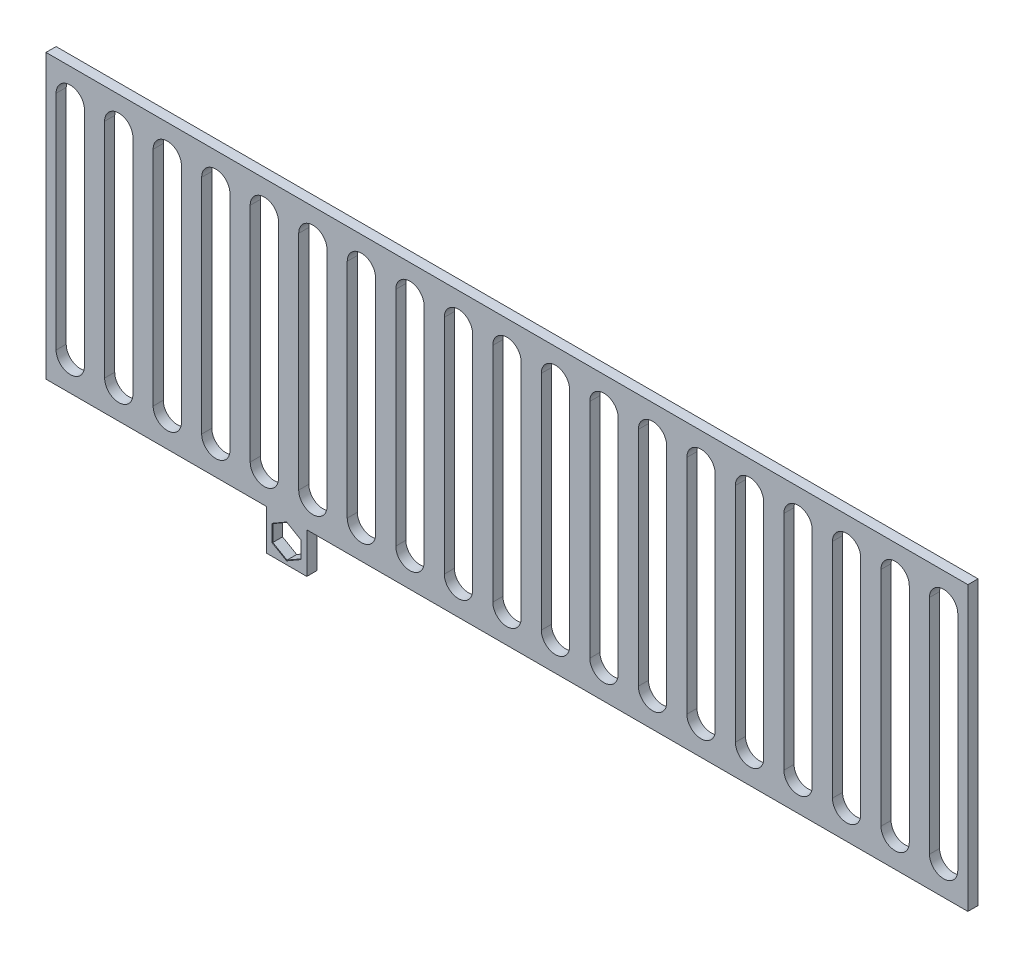
SolidWorks part; units mm, degrees
ref_plane "Plan de face" through (0, 0, 0) normal (0, 0, 1) x (1, 0, 0)
ref_plane "Plan de dessus" through (0, 0, 0) normal (0, 1, 0) x (1, 0, 0)
ref_plane "Plan de droite" through (0, 0, 0) normal (1, 0, 0) x (0, 0, -1)
sketch "Esquisse1" plane through (0, 0, 0) normal (0, 0, 1) x (1, 0, 0)
  line L0 (-108, -27.5) -> (-108, 27.5) construction
  line L1 (-114, 35) -> (114, 35)
  line L2 (-114, 35) -> (-114, -35)
  line L3 (-114, -35) -> (-59.5, -35)
  line L4 (114, 35) -> (114, -35)
  line L5 (-114, 35) -> (114, -35) construction
  line L6 (-114, -35) -> (114, 35) construction
  line L7 (-111.5, -27.5) -> (-111.5, 27.5)
  line L8 (-104.5, -27.5) -> (-104.5, 27.5)
  line L9 (-92.5, -27.5) -> (-92.5, 27.5)
  line L10 (-99.5, -27.5) -> (-99.5, 27.5)
  line L11 (-96, -27.5) -> (-96, 27.5) construction
  line L12 (-80.5, -27.5) -> (-80.5, 27.5)
  line L13 (-87.5, -27.5) -> (-87.5, 27.5)
  line L14 (-84, -27.5) -> (-84, 27.5) construction
  line L15 (-68.5, -27.5) -> (-68.5, 27.5)
  line L16 (-75.5, -27.5) -> (-75.5, 27.5)
  line L17 (-72, -27.5) -> (-72, 27.5) construction
  line L18 (-56.5, -27.5) -> (-56.5, 27.5)
  line L19 (-63.5, -27.5) -> (-63.5, 27.5)
  line L20 (-60, -27.5) -> (-60, 27.5) construction
  line L21 (-44.5, -27.5) -> (-44.5, 27.5)
  line L22 (-51.5, -27.5) -> (-51.5, 27.5)
  line L23 (-48, -27.5) -> (-48, 27.5) construction
  line L24 (-32.5, -27.5) -> (-32.5, 27.5)
  line L25 (-39.5, -27.5) -> (-39.5, 27.5)
  line L26 (-36, -27.5) -> (-36, 27.5) construction
  line L27 (-20.5, -27.5) -> (-20.5, 27.5)
  line L28 (-27.5, -27.5) -> (-27.5, 27.5)
  line L29 (-24, -27.5) -> (-24, 27.5) construction
  line L30 (-8.5, -27.5) -> (-8.5, 27.5)
  line L31 (-15.5, -27.5) -> (-15.5, 27.5)
  line L32 (-12, -27.5) -> (-12, 27.5) construction
  line L33 (3.5, -27.5) -> (3.5, 27.5)
  line L34 (-3.5, -27.5) -> (-3.5, 27.5)
  line L35 (0, -27.5) -> (0, 27.5) construction
  line L36 (15.5, -27.5) -> (15.5, 27.5)
  line L37 (8.5, -27.5) -> (8.5, 27.5)
  line L38 (12, -27.5) -> (12, 27.5) construction
  line L39 (27.5, -27.5) -> (27.5, 27.5)
  line L40 (20.5, -27.5) -> (20.5, 27.5)
  line L41 (24, -27.5) -> (24, 27.5) construction
  line L42 (39.5, -27.5) -> (39.5, 27.5)
  line L43 (32.5, -27.5) -> (32.5, 27.5)
  line L44 (36, -27.5) -> (36, 27.5) construction
  line L45 (51.5, -27.5) -> (51.5, 27.5)
  line L46 (44.5, -27.5) -> (44.5, 27.5)
  line L47 (48, -27.5) -> (48, 27.5) construction
  line L48 (63.5, -27.5) -> (63.5, 27.5)
  line L49 (56.5, -27.5) -> (56.5, 27.5)
  line L50 (60, -27.5) -> (60, 27.5) construction
  line L51 (75.5, -27.5) -> (75.5, 27.5)
  line L52 (68.5, -27.5) -> (68.5, 27.5)
  line L53 (72, -27.5) -> (72, 27.5) construction
  line L54 (87.5, -27.5) -> (87.5, 27.5)
  line L55 (80.5, -27.5) -> (80.5, 27.5)
  line L56 (84, -27.5) -> (84, 27.5) construction
  line L57 (99.5, -27.5) -> (99.5, 27.5)
  line L58 (92.5, -27.5) -> (92.5, 27.5)
  line L59 (96, -27.5) -> (96, 27.5) construction
  line L60 (111.5, -27.5) -> (111.5, 27.5)
  line L61 (104.5, -27.5) -> (104.5, 27.5)
  line L62 (108, -27.5) -> (108, 27.5) construction
  line L69 (-49.5, -35) -> (114, -35)
  line L70 (-59.5, -45) -> (-49.5, -45)
  line L71 (-59.5, -45) -> (-59.5, -35)
  line L73 (-49.5, -45) -> (-49.5, -35)
  line L74 (-59.5, -45) -> (-49.5, -35) construction
  line L75 (-59.5, -35) -> (-49.5, -45) construction
  line L76 (-51, -42.0207) -> (-51, -37.9793)
  line L77 (-51, -37.9793) -> (-54.5, -35.9585)
  line L78 (-54.5, -35.9585) -> (-58, -37.9793)
  line L79 (-58, -37.9793) -> (-58, -42.0207)
  line L80 (-58, -42.0207) -> (-54.5, -44.0415)
  line L81 (-54.5, -44.0415) -> (-51, -42.0207)
  line L82 (123.5, -27.5) -> (123.5, 27.5) [skipped]
  line L83 (128.5, -27.5) -> (128.5, 27.5) [skipped]
  line L84 (135.5, -27.5) -> (135.5, 27.5) [skipped]
  line L85 (116.5, -27.5) -> (116.5, 27.5) [skipped]
  arc A0 (-111.5, -27.5) -> (-104.5, -27.5) centre (-108, -27.5) ccw
  arc A1 (-104.5, 27.5) -> (-111.5, 27.5) centre (-108, 27.5) ccw
  arc A2 (-99.5, -27.5) -> (-92.5, -27.5) centre (-96, -27.5) ccw
  arc A3 (-92.5, 27.5) -> (-99.5, 27.5) centre (-96, 27.5) ccw
  arc A4 (-87.5, -27.5) -> (-80.5, -27.5) centre (-84, -27.5) ccw
  arc A5 (-80.5, 27.5) -> (-87.5, 27.5) centre (-84, 27.5) ccw
  arc A6 (-75.5, -27.5) -> (-68.5, -27.5) centre (-72, -27.5) ccw
  arc A7 (-68.5, 27.5) -> (-75.5, 27.5) centre (-72, 27.5) ccw
  arc A8 (-63.5, -27.5) -> (-56.5, -27.5) centre (-60, -27.5) ccw
  arc A9 (-56.5, 27.5) -> (-63.5, 27.5) centre (-60, 27.5) ccw
  arc A10 (-51.5, -27.5) -> (-44.5, -27.5) centre (-48, -27.5) ccw
  arc A11 (-44.5, 27.5) -> (-51.5, 27.5) centre (-48, 27.5) ccw
  arc A12 (-39.5, -27.5) -> (-32.5, -27.5) centre (-36, -27.5) ccw
  arc A13 (-32.5, 27.5) -> (-39.5, 27.5) centre (-36, 27.5) ccw
  arc A14 (-27.5, -27.5) -> (-20.5, -27.5) centre (-24, -27.5) ccw
  arc A15 (-20.5, 27.5) -> (-27.5, 27.5) centre (-24, 27.5) ccw
  arc A16 (-15.5, -27.5) -> (-8.5, -27.5) centre (-12, -27.5) ccw
  arc A17 (-8.5, 27.5) -> (-15.5, 27.5) centre (-12, 27.5) ccw
  arc A18 (-3.5, -27.5) -> (3.5, -27.5) centre (0, -27.5) ccw
  arc A19 (3.5, 27.5) -> (-3.5, 27.5) centre (0, 27.5) ccw
  arc A20 (8.5, -27.5) -> (15.5, -27.5) centre (12, -27.5) ccw
  arc A21 (15.5, 27.5) -> (8.5, 27.5) centre (12, 27.5) ccw
  arc A22 (20.5, -27.5) -> (27.5, -27.5) centre (24, -27.5) ccw
  arc A23 (27.5, 27.5) -> (20.5, 27.5) centre (24, 27.5) ccw
  arc A24 (32.5, -27.5) -> (39.5, -27.5) centre (36, -27.5) ccw
  arc A25 (39.5, 27.5) -> (32.5, 27.5) centre (36, 27.5) ccw
  arc A26 (44.5, -27.5) -> (51.5, -27.5) centre (48, -27.5) ccw
  arc A27 (51.5, 27.5) -> (44.5, 27.5) centre (48, 27.5) ccw
  arc A28 (56.5, -27.5) -> (63.5, -27.5) centre (60, -27.5) ccw
  arc A29 (63.5, 27.5) -> (56.5, 27.5) centre (60, 27.5) ccw
  arc A30 (68.5, -27.5) -> (75.5, -27.5) centre (72, -27.5) ccw
  arc A31 (75.5, 27.5) -> (68.5, 27.5) centre (72, 27.5) ccw
  arc A32 (80.5, -27.5) -> (87.5, -27.5) centre (84, -27.5) ccw
  arc A33 (87.5, 27.5) -> (80.5, 27.5) centre (84, 27.5) ccw
  arc A34 (92.5, -27.5) -> (99.5, -27.5) centre (96, -27.5) ccw
  arc A35 (99.5, 27.5) -> (92.5, 27.5) centre (96, 27.5) ccw
  arc A36 (104.5, -27.5) -> (111.5, -27.5) centre (108, -27.5) ccw
  arc A37 (111.5, 27.5) -> (104.5, 27.5) centre (108, 27.5) ccw
  circle A42 centre (-54.5, -40) radius 3.5 construction
  arc A43 (123.5, 27.5) -> (116.5, 27.5) centre (120, 27.5) ccw [skipped]
  arc A44 (128.5, -27.5) -> (135.5, -27.5) centre (132, -27.5) ccw [skipped]
  arc A45 (135.5, 27.5) -> (128.5, 27.5) centre (132, 27.5) ccw [skipped]
  arc A46 (116.5, -27.5) -> (123.5, -27.5) centre (120, -27.5) ccw [skipped]
  point P0 (0, 0)
  point P8 (-108, 0)
  point P14 (-54.5, -40)
  point P16 (-96, 0)
  point P23 (-84, 0)
  point P30 (-72, 0)
  point P37 (-60, 0)
  point P44 (-48, 0)
  point P51 (-36, 0)
  point P58 (-24, 0)
  point P65 (-12, 0)
  point P72 (0, 0)
  point P79 (12, 0)
  point P86 (24, 0)
  point P93 (36, 0)
  point P100 (48, 0)
  point P107 (60, 0)
  point P114 (72, 0)
  point P121 (84, 0)
  point P128 (96, 0)
  point P135 (108, 0)
  dimension "D4" = 3.5
  dimension "D1" = 228
  dimension "D2" = 70
  dimension "D3" = 55
  dimension "D5" = 6
  dimension "D7" = 10
  dimension "D8" = 10
  dimension "D9" = 7
  dimension "D10" = 12
  dimension "D6" = 21
extrude "Boss.-Extru.1" add sketch "Esquisse1" along normal blind 2.5
chamfer "Chanfrein1" distance 0.1 angle 45 6 edges at (-51, -40, 2.5) (-52.75, -43.0311, 2.5) (-56.25, -43.0311, 2.5) (-58, -40, 2.5) (-52.75, -36.9689, 2.5) (-56.25, -36.9689, 2.5)
